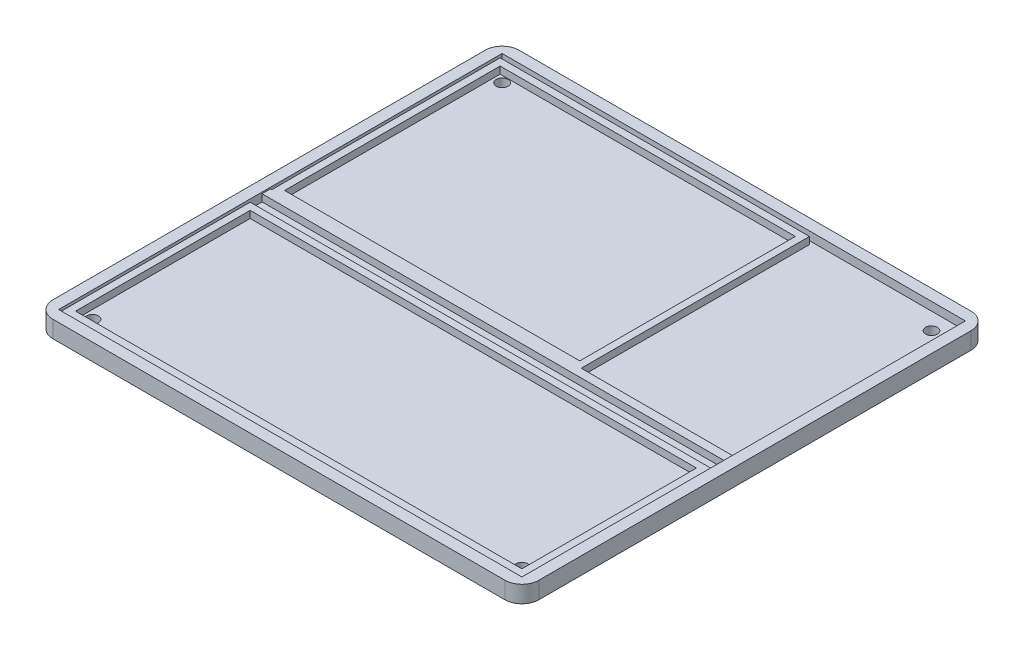
SolidWorks part; units mm, degrees
ref_plane "Front Plane" through (0, 0, 0) normal (0, 0, 1) x (1, 0, 0)
ref_plane "Top Plane" through (0, 0, 0) normal (0, 1, 0) x (1, 0, 0)
ref_plane "Right Plane" through (0, 0, 0) normal (1, 0, 0) x (0, 0, -1)
sketch "Sk_Outline" plane through (0, 0, 0) normal (0, 1, 0) x (1, 0, 0)
  line L0 (6, 0) -> (166, 0)
  line L1 (172, 6) -> (172, 159)
  line L2 (166, 165) -> (6, 165)
  line L3 (0, 159) -> (0, 6)
  arc A0 (166, 0) -> (172, 6) centre (166, 6) ccw
  arc A1 (172, 159) -> (166, 165) centre (166, 159) ccw
  arc A2 (6, 165) -> (0, 159) centre (6, 159) ccw
  arc A3 (0, 6) -> (6, 0) centre (6, 6) ccw
extrude "Tray Body" add sketch "Sk_Outline" along normal blind 6
ref_plane "Plane_TrayFloor" through (0, 3, 0) normal (0, 1, 0) x (1, 0, 0)
sketch "Sk_Pocket" plane through (0, 3, 0) normal (0, 1, 0) x (1, 0, 0)
  line L1 (4, 4) -> (168, 4)
  line L2 (4, 4) -> (4, 161)
  line L3 (4, 161) -> (168, 161)
  line L4 (168, 4) -> (168, 161)
extrude "Tray Pocket" cut sketch "Sk_Pocket" along normal through all
sketch "Sk_ESP32Guide" plane through (0, 3, 0) normal (0, 1, 0) x (1, 0, 0)
  line L1 (4.5, 4.5) -> (167.5, 4.5)
  line L2 (4.5, 4.5) -> (4.5, 71.3)
  line L3 (4.5, 71.3) -> (167.5, 71.3)
  line L4 (167.5, 4.5) -> (167.5, 71.3)
  line L6 (7, 7) -> (165, 7)
  line L7 (7, 7) -> (7, 68.8)
  line L8 (7, 68.8) -> (165, 68.8)
  line L9 (165, 7) -> (165, 68.8)
extrude "ESP32 Housing Guide" add sketch "Sk_ESP32Guide" along normal blind 2.5
sketch "Sk_Pi5Guide" plane through (0, 3, 0) normal (0, 1, 0) x (1, 0, 0)
  line L1 (4.5, 78.5) -> (114, 78.5)
  line L2 (4.5, 78.5) -> (4.5, 159.8)
  line L3 (4.5, 159.8) -> (114, 159.8)
  line L4 (114, 78.5) -> (114, 159.8)
  line L6 (7, 81) -> (111.5, 81)
  line L7 (7, 81) -> (7, 157.3)
  line L8 (7, 157.3) -> (111.5, 157.3)
  line L9 (111.5, 81) -> (111.5, 157.3)
extrude "Pi5 Cage Guide" add sketch "Sk_Pi5Guide" along normal blind 2.5
sketch "Sk_Divider" plane through (0, 3, 0) normal (0, 1, 0) x (1, 0, 0)
  line L1 (4, 76) -> (168, 76)
  line L2 (4, 76) -> (4, 79)
  line L3 (4, 79) -> (168, 79)
  line L4 (168, 76) -> (168, 79)
extrude "Center Divider" add sketch "Sk_Divider" along normal blind 2.5
sketch "Sk_MountHoles" plane through (0, 0, 0) normal (0, 1, 0) x (1, 0, 0)
  circle A0 centre (10, 10) radius 2.1
  circle A1 centre (10, 155) radius 2.1
  circle A2 centre (162, 10) radius 2.1
  circle A3 centre (162, 155) radius 2.1
extrude "M4 Mounting Holes" cut sketch "Sk_MountHoles" against normal through all and the other way through all
